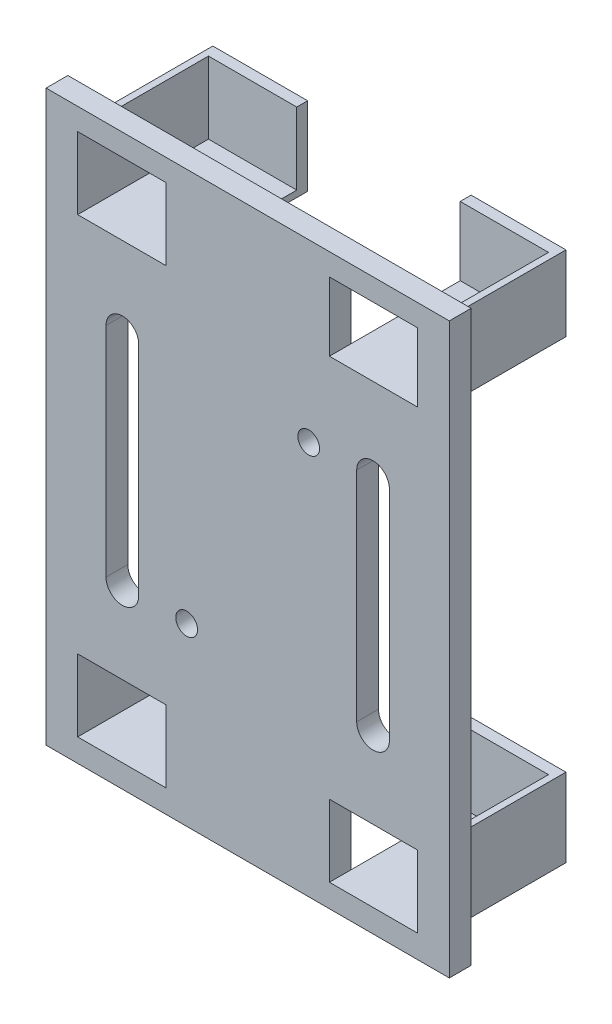
SolidWorks part; units mm, degrees
ref_plane "Front Plane" through (0, 0, 0) normal (0, 0, 1) x (1, 0, 0)
ref_plane "Top Plane" through (0, 0, 0) normal (0, 1, 0) x (1, 0, 0)
ref_plane "Right Plane" through (0, 0, 0) normal (1, 0, 0) x (0, 0, -1)
sketch "Sketch1" plane through (0, 0, 0) normal (0, 0, 1) x (1, 0, 0)
  line L1 (39.624, 45.212) -> (19.05, 45.212)
  line L2 (46.99, -66.3146) -> (-46.99, -66.3146)
  line L3 (46.99, -66.3146) -> (46.99, 66.3146)
  line L4 (46.99, 66.3146) -> (-46.99, 66.3146)
  line L5 (-46.99, -66.3146) -> (-46.99, 66.3146)
  line L6 (46.99, -66.3146) -> (-46.99, 66.3146) construction
  line L7 (46.99, 66.3146) -> (-46.99, -66.3146) construction
  line L8 (14.224, -25.4) -> (-14.224, -25.4) construction
  line L9 (14.224, -25.4) -> (14.224, 25.4) construction
  line L10 (14.224, 25.4) -> (-14.224, 25.4) construction
  line L11 (-14.224, -25.4) -> (-14.224, 25.4) construction
  line L12 (14.224, -25.4) -> (-14.224, 25.4) construction
  line L13 (14.224, 25.4) -> (-14.224, -25.4) construction
  line L14 (39.624, 45.212) -> (39.624, 61.214)
  line L15 (39.624, 61.214) -> (19.05, 61.214)
  line L16 (19.05, 45.212) -> (19.05, 61.214)
  line L17 (39.624, 45.212) -> (19.05, 61.214) construction
  line L18 (39.624, 61.214) -> (19.05, 45.212) construction
  line L19 (-39.624, -44.196) -> (-19.05, -44.196)
  line L20 (-39.624, -44.196) -> (-39.624, -60.96)
  line L21 (-39.624, -60.96) -> (-19.05, -60.96)
  line L22 (-19.05, -44.196) -> (-19.05, -60.96)
  line L23 (-39.624, -44.196) -> (-19.05, -60.96) construction
  line L24 (-39.624, -60.96) -> (-19.05, -44.196) construction
  line L25 (-19.05, 44.45) -> (-39.624, 44.45)
  line L26 (-19.05, 44.45) -> (-19.05, 61.214)
  line L27 (-19.05, 61.214) -> (-39.624, 61.214)
  line L28 (-39.624, 44.45) -> (-39.624, 61.214)
  line L29 (-19.05, 44.45) -> (-39.624, 61.214) construction
  line L30 (-19.05, 61.214) -> (-39.624, 44.45) construction
  line L31 (19.05, -44.196) -> (39.624, -44.196)
  line L32 (19.05, -44.196) -> (19.05, -60.96)
  line L33 (19.05, -60.96) -> (39.624, -60.96)
  line L34 (39.624, -44.196) -> (39.624, -60.96)
  line L35 (19.05, -44.196) -> (39.624, -60.96) construction
  line L36 (19.05, -60.96) -> (39.624, -44.196) construction
  line L38 (-33.02, -25.4) -> (-33.02, 25.4)
  line L40 (-25.4, -25.4) -> (-25.4, 25.4)
  line L41 (-33.02, -25.4) -> (-25.4, 25.4) construction
  line L42 (-33.02, 25.4) -> (-25.4, -25.4) construction
  line L45 (25.4, -25.4) -> (25.4, 25.4)
  line L47 (33.02, -25.4) -> (33.02, 25.4)
  line L48 (25.4, -25.4) -> (33.02, 25.4) construction
  line L49 (25.4, 25.4) -> (33.02, -25.4) construction
  circle A0 centre (-14.224, -25.4) radius 2.54
  circle A1 centre (14.224, 25.4) radius 2.54
  arc A2 (-33.02, 25.4) -> (-25.4, 25.4) centre (-29.21, 25.4) cw
  arc A3 (-25.4, -25.4) -> (-33.02, -25.4) centre (-29.21, -25.4) cw
  arc A4 (25.4, 25.4) -> (33.02, 25.4) centre (29.21, 25.4) cw
  arc A5 (33.02, -25.4) -> (25.4, -25.4) centre (29.21, -25.4) cw
  point P0 (0, 0)
  point P1 (0, 0)
  point P13 (29.337, 53.213)
  point P18 (-29.337, -52.578)
  point P23 (-29.337, 52.832)
  point P28 (29.337, -52.578)
  point P33 (-29.21, 0)
  point P39 (29.21, 0)
  dimension "D5" = 5.08
  dimension "D6" = 5.08
  dimension "D1" = 50.8
  dimension "D2" = 28.448
  dimension "D3" = 132.6292
  dimension "D4" = 93.98
  dimension "D7" = 16.002
  dimension "D8" = 20.574
  dimension "D9" = 4.826
  dimension "D10" = 35.814
  dimension "D11" = 35.56
  dimension "D12" = 4.826
  dimension "D13" = 20.574
  dimension "D14" = 16.764
  dimension "D15" = 16.764
  dimension "D16" = 20.574
  dimension "D17" = 20.574
  dimension "D18" = 38.1
  dimension ".63" = 16.764
  dimension "D19" = 38.1
  dimension "D20" = 35.56
  dimension "D21" = 35.814
  dimension "D22" = 7.62
  dimension "D23" = 7.62
  dimension "D24" = 29.21
  dimension "D25" = 29.21
  dimension "D26" = 50.8
  dimension "D27" = 50.8
extrude "Boss-Extrude1" add sketch "Sketch1" along normal blind 5.08
sketch "Sketch3" plane through (0, 0, 0) normal (0, 0, -1) x (-1, 0, 0)
  line L9 (-19.05, 45.212) -> (-39.624, 45.212)
  line L10 (-39.624, 45.212) -> (-39.624, 61.214)
  line L11 (-39.624, 61.214) -> (-41.148, 61.214)
  line L12 (-19.05, 45.212) -> (-19.05, 43.688)
  line L13 (-19.05, -59.563) -> (-19.05, 59.563) construction
  line L14 (-41.148, 61.214) -> (-41.148, 43.688)
  line L15 (-19.05, 43.688) -> (-41.148, 43.688)
  line L16 (19.05, 44.45) -> (39.624, 44.45)
  line L17 (39.624, 44.45) -> (39.624, 61.214)
  line L18 (39.624, 61.214) -> (41.148, 61.214)
  line L19 (19.05, 44.45) -> (19.05, 42.926)
  line L20 (19.05, 59.563) -> (19.05, -59.563) construction
  line L21 (19.05, -60.96) -> (39.624, -60.96)
  line L22 (39.624, -60.96) -> (39.624, -44.196)
  line L23 (39.624, -44.196) -> (41.148, -44.196)
  line L24 (19.05, -60.96) -> (19.05, -62.484)
  line L25 (-39.624, -44.196) -> (-39.624, -60.96)
  line L26 (-39.624, -60.96) -> (-19.05, -60.96)
  line L27 (-19.05, -60.96) -> (-19.05, -62.484)
  line L28 (-39.624, -44.196) -> (-41.148, -44.196)
  line L29 (41.148, 61.214) -> (41.148, 42.926)
  line L30 (19.05, 42.926) -> (41.148, 42.926)
  line L31 (19.05, -62.484) -> (41.148, -62.484)
  line L32 (41.148, -44.196) -> (41.148, -62.484)
  line L33 (-19.05, -62.484) -> (-41.148, -62.484)
  line L34 (-41.148, -44.196) -> (-41.148, -62.484)
  dimension "D1" = 1.524
  dimension "D2" = 1.524
  dimension "D3" = 1.524
  dimension "D4" = 1.524
  dimension "D5" = 1.524
  dimension "D6" = 1.524
  dimension "D7" = 1.524
  dimension "D8" = 1.524
extrude "Boss-Extrude2" add sketch "Sketch3" along normal blind 27.94
sketch "Sketch4" plane through (0, 0, -27.94) normal (0, 0, -1) x (-1, 0, 0)
  line L1 (-41.148, 43.688) -> (-19.05, 43.688)
  line L2 (-41.148, 43.688) -> (-41.148, 61.214)
  line L3 (-41.148, 61.214) -> (-19.05, 61.214)
  line L4 (-19.05, 43.688) -> (-19.05, 61.214)
  line L5 (41.148, 42.926) -> (19.05, 42.926)
  line L6 (41.148, 42.926) -> (41.148, 61.214)
  line L7 (41.148, 61.214) -> (19.05, 61.214)
  line L8 (19.05, 42.926) -> (19.05, 61.214)
  line L9 (41.148, -62.484) -> (19.05, -62.484)
  line L10 (41.148, -62.484) -> (41.148, -44.196)
  line L11 (41.148, -44.196) -> (19.05, -44.196)
  line L12 (19.05, -62.484) -> (19.05, -44.196)
  line L14 (-41.148, -62.484) -> (-19.05, -62.484)
  line L15 (-41.148, -62.484) -> (-41.148, -44.196)
  line L16 (-41.148, -44.196) -> (-19.05, -44.196)
  line L17 (-19.05, -62.484) -> (-19.05, -44.196)
extrude "Boss-Extrude3" add sketch "Sketch4" against normal blind 2.54
